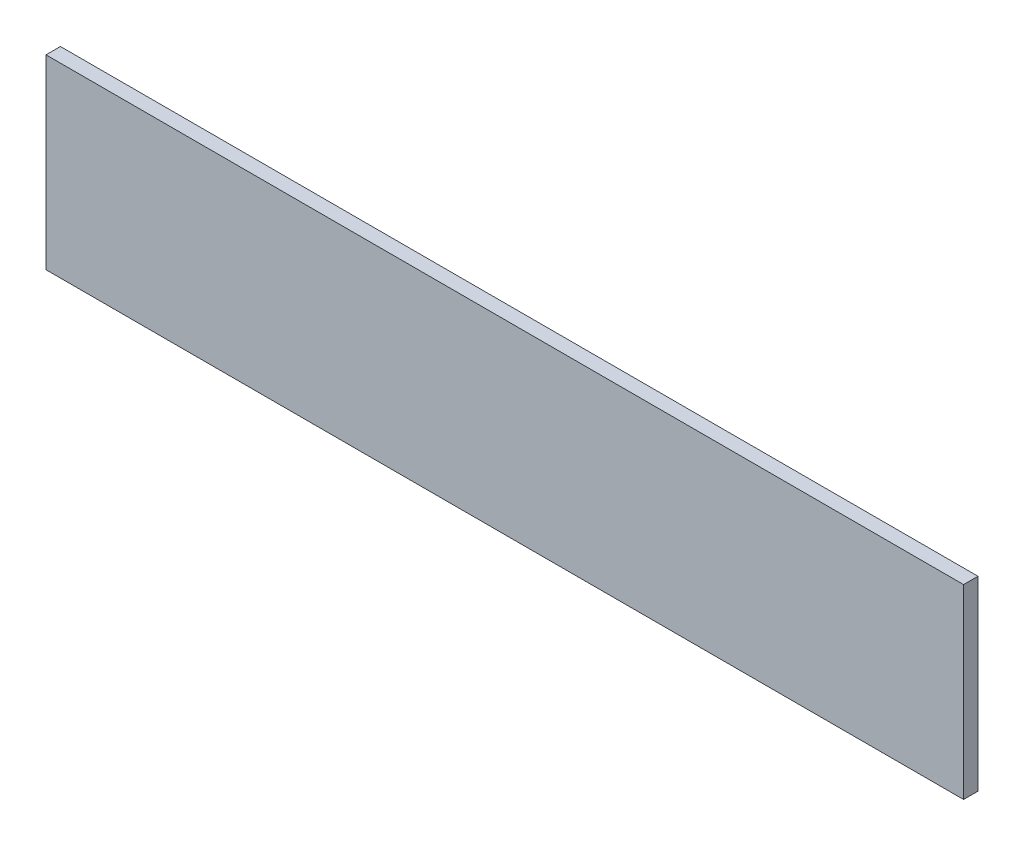
SolidWorks part; units mm, degrees
ref_plane "Alzado" through (0, 0, 0) normal (0, 0, 1) x (1, 0, 0)
ref_plane "Planta" through (0, 0, 0) normal (0, 1, 0) x (1, 0, 0)
ref_plane "Vista lateral" through (0, 0, 0) normal (1, 0, 0) x (0, 0, -1)
sketch "Croquis1" plane through (0, 0, 0) normal (0, 0, 1) x (1, 0, 0)
  line L1 (-99.6319, 40.3681) -> (250.3681, 40.3681)
  line L2 (-99.6319, 40.3681) -> (-99.6319, -30.6319)
  line L3 (-99.6319, -30.6319) -> (250.3681, -30.6319)
  line L4 (250.3681, 40.3681) -> (250.3681, -30.6319)
  dimension "D1" = 350
  dimension "D2" = 71
extrude "Saliente-Extruir1" add sketch "Croquis1" along normal blind 5.5
